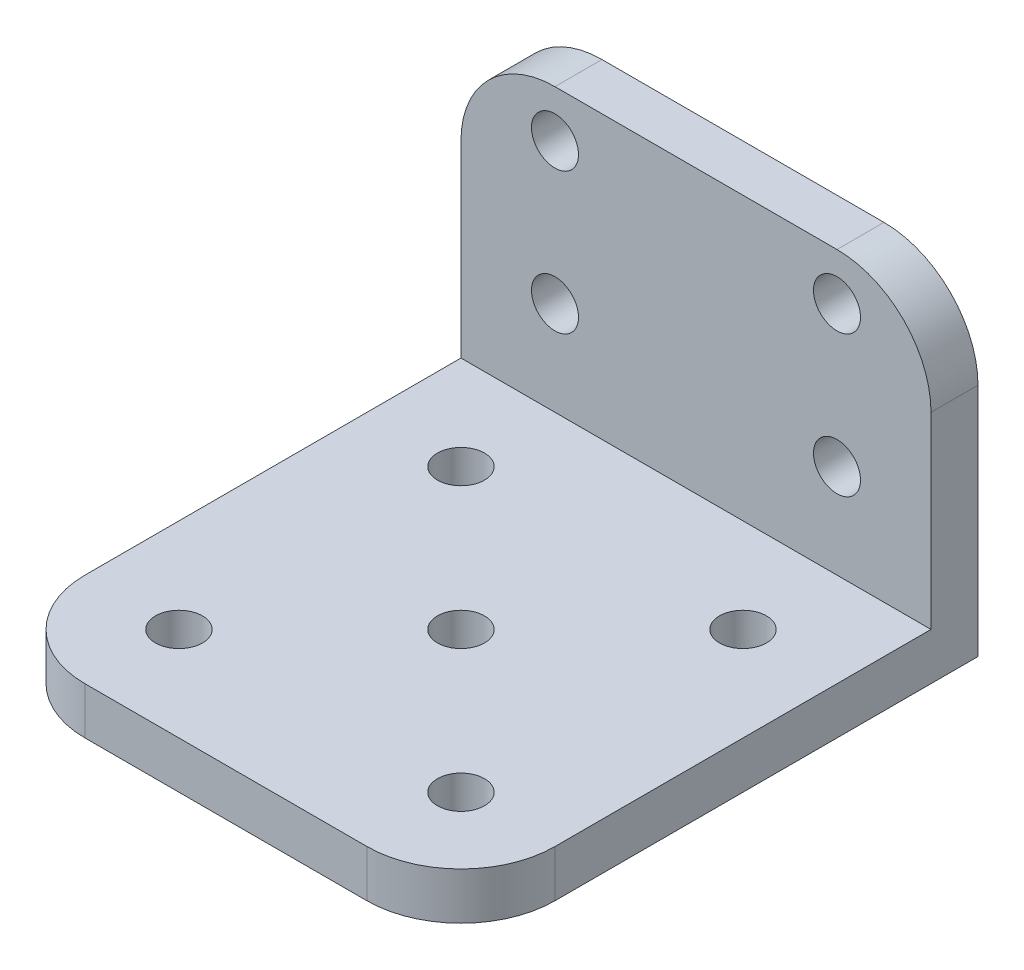
SolidWorks part; units mm, degrees
ref_plane "Front Plane" through (0, 0, 0) normal (0, 0, 1) x (1, 0, 0)
ref_plane "Top Plane" through (0, 0, 0) normal (0, 1, 0) x (1, 0, 0)
ref_plane "Right Plane" through (0, 0, 0) normal (1, 0, 0) x (0, 0, -1)
sketch "Sketch1" plane through (0, 0, 0) normal (0, 0, 1) x (1, 0, 0)
  line L1 (0, 0) -> (50, 0)
  line L2 (0, 0) -> (0, 60)
  line L3 (0, 60) -> (50, 60)
  line L4 (50, 0) -> (50, 60)
  dimension "D1" = 50
  dimension "D2" = 60
extrude "Boss-Extrude1" add sketch "Sketch1" along normal blind 5
sketch "Sketch2" plane through (0, 0, 5) normal (0, 0, 1) x (1, 0, 0)
  line L0 (50, 0) -> (50, 60) construction
  line L1 (0, 0) -> (50, 0)
  line L2 (0, 0) -> (0, 5)
  line L3 (0, 5) -> (50, 5)
  line L4 (50, 0) -> (50, 5)
  dimension "D1" = 5
extrude "Boss-Extrude2" add sketch "Sketch2" along normal blind 50
sketch "Sketch3" plane through (0, 60, 0) normal (0, 1, 0) x (1, 0, 0)
  line L1 (0, 0) -> (50, 0)
  line L2 (0, 0) -> (0, -5)
  line L3 (0, -5) -> (50, -5)
  line L4 (50, 0) -> (50, -5)
extrude "Cut-Extrude1" cut sketch "Sketch3" against normal blind 5
sketch "Sketch4" plane through (0, 5, 0) normal (0, 1, 0) x (1, 0, 0)
  line L0 (0, -5) -> (10, -5)
  line L1 (0, -5) -> (50, -5) construction
  line L2 (10, -5) -> (10, -15)
  line L3 (10, -15) -> (10, -45)
  line L4 (10, -45) -> (40, -45)
  line L5 (40, -45) -> (40, -15)
  line L6 (10, -30) -> (25, -30)
  circle A0 centre (10, -15) radius 2.5
  circle A1 centre (40, -15) radius 2.5
  circle A2 centre (40, -45) radius 2.5
  circle A3 centre (10, -45) radius 2.5
  circle A4 centre (25, -30) radius 2.5
  dimension "D1" = 10
extrude "Cut-Extrude2" cut sketch "Sketch4" against normal blind 5
sketch "Sketch5" plane through (0, 0, 5) normal (0, 0, 1) x (1, 0, 0)
  line L0 (0, 55) -> (10, 55)
  line L1 (0, 55) -> (50, 55) construction
  line L2 (10, 55) -> (10, 45)
  line L3 (10, 45) -> (10, 15)
  line L4 (10, 15) -> (40, 15)
  line L5 (40, 15) -> (40, 45)
  line L6 (40, 45) -> (25, 30)
  circle A0 centre (10, 45) radius 2.5
  circle A1 centre (40, 45) radius 2.5
  circle A2 centre (25, 30) radius 2.5
  circle A3 centre (40, 15) radius 2.5
  circle A4 centre (10, 15) radius 2.5
  dimension "D1" = 10
extrude "Cut-Extrude3" cut sketch "Sketch5" against normal blind 5
fillet "Fillet1" radius 10 4 edges at (50, 55, 2.5) (0, 55, 2.5) (0, 2.5, 55) (50, 2.5, 55)
sketch "Sketch7" plane through (0, 55, 0) normal (0, 1, 0) x (1, 0, 0)
  line L1 (0, 0) -> (50, 0)
  line L2 (0, 0) -> (0, -5)
  line L3 (0, -5) -> (50, -5)
  line L4 (50, 0) -> (50, -5)
extrude "Cut-Extrude4" cut sketch "Sketch7" against normal blind 20
fillet "Fillet2" radius 10 2 edges at (50, 35, 2.5) (0, 35, 2.5)
sketch "Sketch8" plane through (0, 0, 5) normal (0, 0, 1) x (1, 0, 0)
  line L0 (10, 15) -> (25, 30)
  line L1 (25, 30) -> (10, 30)
  line L2 (10, 30) -> (10, 15)
  line L3 (25, 30) -> (40, 30)
  circle A0 centre (10, 30) radius 2.5
  circle A1 centre (40, 30) radius 2.5
extrude "Cut-Extrude5" cut sketch "Sketch8" against normal blind 20
sketch "Sketch9" plane through (0, 0, 5) normal (0, 0, 1) x (1, 0, 0)
  circle A0 centre (25, 30) radius 2.5
extrude "Boss-Extrude3" add sketch "Sketch9" against normal through all
